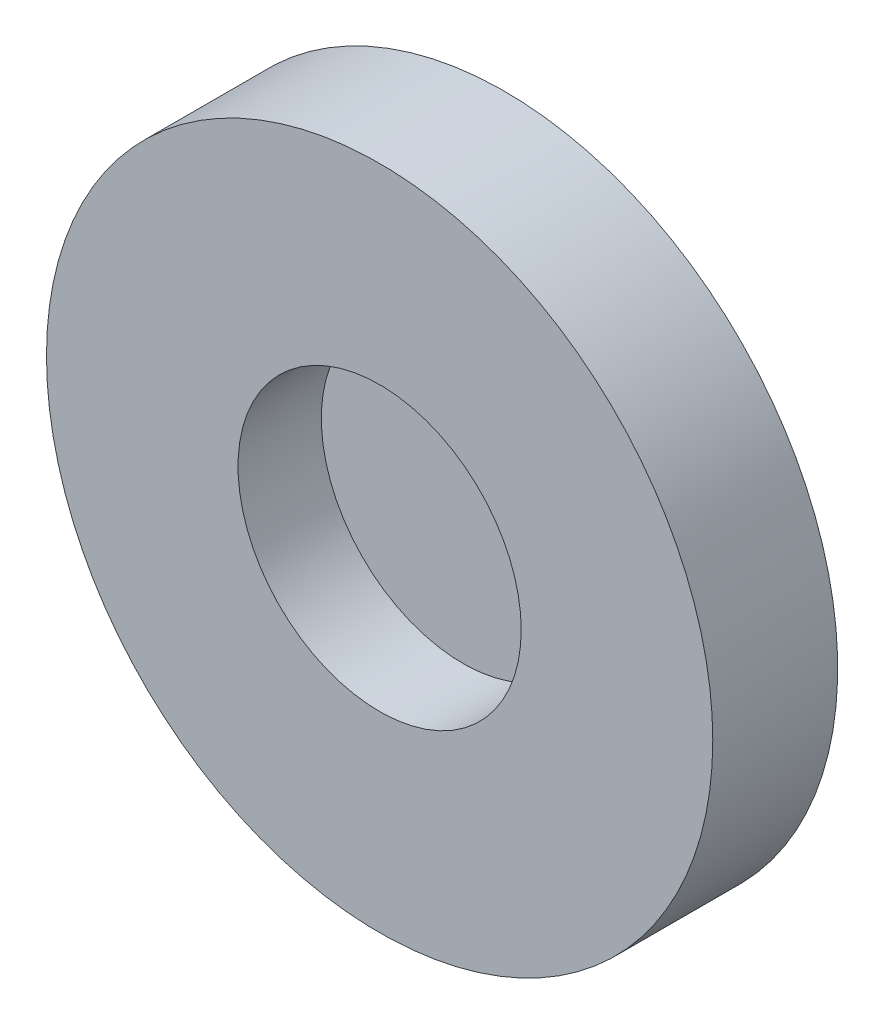
SolidWorks part; units mm, degrees
material "ABS"
ref_plane "Plan de face" through (0, 0, 0) normal (0, 0, 1) x (1, 0, 0)
ref_plane "Plan de dessus" through (0, 0, 0) normal (0, 1, 0) x (1, 0, 0)
ref_plane "Plan de droite" through (0, 0, 0) normal (1, 0, 0) x (0, 0, -1)
sketch "Esquisse1" plane through (0, 0, 0) normal (0, 0, 1) x (1, 0, 0)
  circle A0 centre (0, 0) radius 4
  circle A1 centre (0, 0) radius 1.7
  dimension "D1" = 8
  dimension "D2" = 3.4
extrude "Boss.-Extru.1" add sketch "Esquisse1" along normal blind 1
sketch "Esquisse2" plane through (0, 0, 0) normal (0, 0, -1) x (-1, 0, 0)
  circle A0 centre (0, 0) radius 4
extrude "Boss.-Extru.2" add sketch "Esquisse2" along normal blind 0.5
equation "\"entretoiseBearing\"= 1.5mm"
equation "\"length_tibia\"= 206mm"
equation "\"length_femur\"= 117mm"
equation "\"length_coxa\"= 27mm"
equation "\"height\"= 40mm"
equation "\"width\"= 100mm"
equation "\"lever\"= 40mm"
equation "\"errorFlat\"= 0.20mm"
equation "\"errorFlat_tight\"= 0.15mm"
equation "\"errorCircle\"= 0.40mm"
equation "\"errorCircle_tight\" = 0.30mm"
equation "\"cuticule\"=1.5mm"
equation "\"cuticule_attach_w\"=10mm"
equation "\"cuticule_attach_h\"=2.5mm"
equation "\"depthMagnet\"= 1mm"
equation "\"insert_d\" = 3.2mm"
equation "\"insert_l\" = 5mm"
equation "\"D2@Esquisse1\"= 3 + \"errorCircle\""
